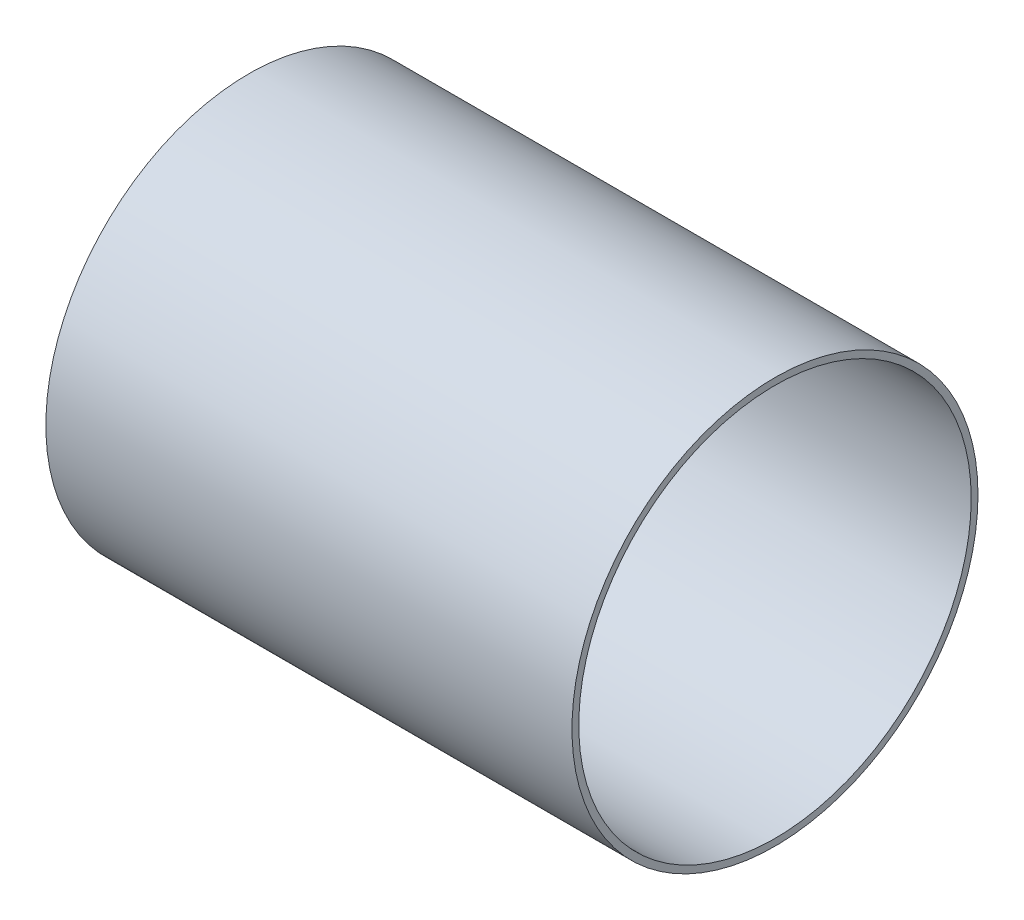
SolidWorks part; units mm, degrees
ref_plane "Plano frontal" through (0, 0, 0) normal (0, 0, 1) x (1, 0, 0)
ref_plane "Plano superior" through (0, 0, 0) normal (0, 1, 0) x (1, 0, 0)
ref_plane "Plano direito" through (0, 0, 0) normal (1, 0, 0) x (0, 0, -1)
sketch "Esboço1" plane through (0, 0, 0) normal (1, 0, 0) x (0, 0, -1)
  circle A0 centre (0, 0) radius 10.765
  circle A1 centre (0, 0) radius 10.405
  dimension "D1" = 21.53
  dimension "D2" = 0.36
extrude "Ressalto-extrusão3" add sketch "Esboço1" along normal blind 27.9
